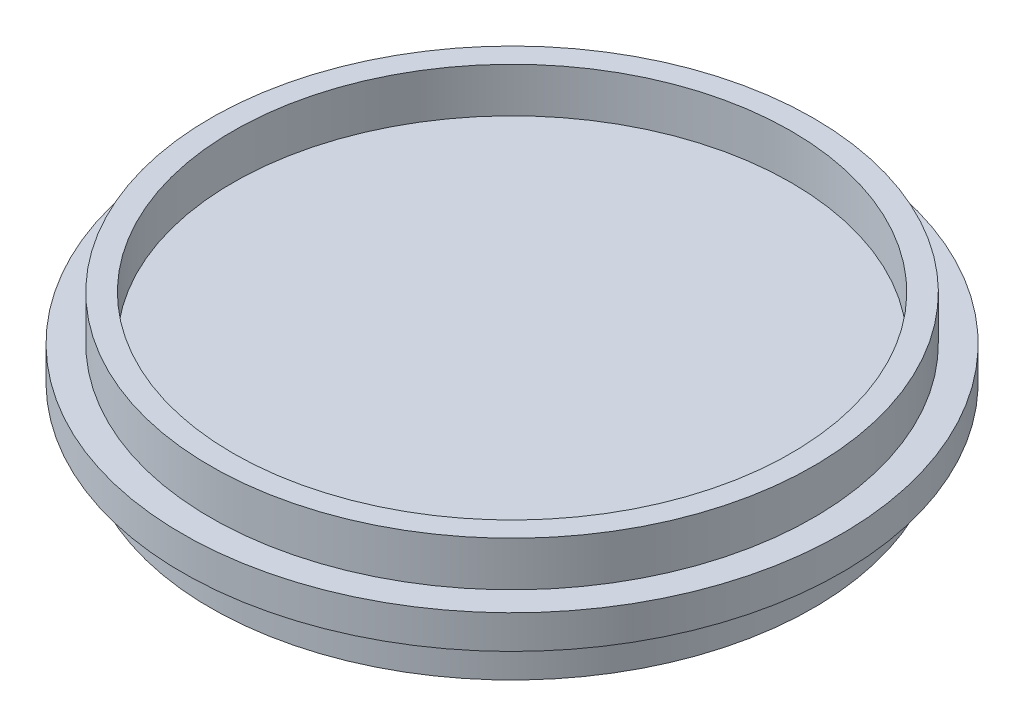
SolidWorks part; units mm, degrees
material "6061-T6 (SS)"
ref_plane "Front Plane" through (0, 0, 0) normal (0, 0, 1) x (1, 0, 0)
ref_plane "Top Plane" through (0, 0, 0) normal (0, 1, 0) x (1, 0, 0)
ref_plane "Right Plane" through (0, 0, 0) normal (1, 0, 0) x (0, 0, -1)
sketch "Sketch1" plane through (0, 0, 0) normal (0, 1, 0) x (1, 0, 0)
  line L5 (0, 0) -> (127.635, 0)
  line L6 (0, 0) -> (0, 127.635)
  line L7 (0, 127.635) -> (127.635, 127.635)
  line L8 (127.635, 0) -> (127.635, 127.635)
  dimension "D1" = 127.635
  dimension "D2" = 127.635
extrude "Boss-Extrude1" add sketch "Sketch1" along normal blind 9.525 contours L5 L8 L7 L6
sketch "Sketch12" plane through (0, 0, 0) normal (0, -1, 0) x (1, 0, 0)
  line L0 (63.8175, 0) -> (63.8175, -127.635) construction
  line L1 (0, 0) -> (127.635, 0) construction
  line L2 (0, -127.635) -> (127.635, -127.635) construction
  line L3 (0, -63.8175) -> (127.635, -63.8175) construction
  line L4 (0, 0) -> (0, -127.635) construction
  line L5 (127.635, 0) -> (127.635, -127.635) construction
  circle A0 centre (63.8175, -63.8175) radius 93.726
  dimension "D1" = 187.452
extrude "Boss-Extrude2" add sketch "Sketch12" against normal up to surface (9.525 mm away) contours A0 up to face at (63.8175, 9.525, -63.8175)
sketch "Sketch5" plane through (0, 9.525, 0) normal (0, 1, 0) x (1, 0, 0)
  circle A0 centre (63.8175, 63.8175) radius 46.355
  circle A3 centre (63.8175, 63.8175) radius 93.726 construction
  dimension "D1" = 92.71
extrude "Cut-Extrude1" [suppressed] cut sketch "Sketch5" against normal blind 9.525
sketch "Sketch11" [suppressed] plane through (0, 9.525, 0) normal (0, 1, 0) x (1, 0, 0)
  line L0 (63.8175, 63.8175) -> (63.8175, 115.443) construction
  circle A0 centre (63.8175, 115.443) radius 1.4351
  dimension "D2" = 2.8702
  dimension "D1" = 51.6255
extrude "Cut-Extrude3" [suppressed] cut sketch "Sketch11" against normal through all contours A0
pattern_circular "CirPattern1" [suppressed] count 12 over 360
sketch "Sketch14" [suppressed] plane through (0, 9.525, 0) normal (0, -1, 0) x (1, 0, 0)
  line L0 (63.8175, -63.8175) -> (147.6375, -63.8175) construction
  line L1 (0, -19.2087) -> (0, 19.2087) construction
  line L2 (147.6375, -63.8175) -> (152.7175, -63.8175)
  line L3 (136.3808, -105.7742) -> (140.8401, -108.2104)
  circle A0 centre (63.8175, -63.8175) radius 46.355 construction
  arc A2 (147.6375, -63.8175) -> (136.3808, -105.7742) centre (63.8175, -63.8175) cw
  arc A3 (152.7175, -63.8175) -> (140.8401, -108.2104) centre (63.8175, -63.8175) cw
  point P0 (63.8175, -63.8175)
  dimension "D1" = 83.82
  dimension "D2" = 88.9
  dimension "D3" = 46.482
  dimension "D4" = 43.942
ref_plane "Support mirror reference plane" through (0, 4.7625, 0) normal (0, 1, 0) x (1, 0, 0)
sketch "Sketch25" [suppressed] plane through (0, 9.525, 0) normal (0, -1, 0) x (1, 0, 0)
  line L0 (63.8175, -63.8175) -> (123.0872, -4.5478) construction
  line L2 (123.0872, -4.5478) -> (126.6793, -0.9557)
  line L3 (144.7953, -42.1754) -> (149.6712, -40.7448)
  line L5 (63.8175, -63.8175) -> (147.6375, -63.8175) construction
  arc A2 (123.0872, -4.5478) -> (144.7953, -42.1754) centre (63.8175, -63.8175) cw
  arc A3 (126.6793, -0.9557) -> (149.6712, -40.7448) centre (63.8175, -63.8175) cw
  point P0 (63.8175, -63.8175)
  dimension "D1" = 83.82
  dimension "D2" = 88.9
  dimension "D3" = 46.482
  dimension "D4" = 43.942
  dimension "D5" = 45
sketch "Sketch30" plane through (0, 0, 0) normal (0, -1, 0) x (1, 0, 0)
  circle A0 centre (63.8175, -63.8175) radius 85.725
  circle A1 centre (63.8175, -63.8175) radius 79.375
  dimension "D1" = 171.45
  dimension "D2" = 158.75
extrude "Boss-Extrude3" add sketch "Sketch30" along normal blind 12.7
mirror "Mirror1" about plane through (0, 4.7625, 0) normal (0, 1, 0) of "Boss-Extrude3"
sketch "Sketch31" plane through (0, 0, 0) normal (0, -1, 0) x (-1, 0, 0)
  line L0 (-63.8175, -52.481) -> (-63.8175, 177.7216) construction
ref_plane "Plane1" through (0, 0, -149.5425) normal (0, 0, -1) x (-1, 0, 0)
ref_plane "Plane2" through (63.8175, 0, 0) normal (-1, 0, 0) x (0, 0, -1)
sketch "Sketch32" plane through (0, 0, -149.5425) normal (0, 0, -1) x (-1, 0, 0)
  line L4 (-63.8175, -87.3125) -> (-63.8175, 87.3125) construction
  line L5 (-149.5425, 0) -> (21.9075, 0) construction
  line L6 (21.9075, 9.525) -> (-149.5425, 9.525) construction
  circle A0 centre (-63.8175, -6.35) radius 1.4351
  circle A1 centre (-63.8175, 15.875) radius 1.4351
  dimension "D1" = 2.8702
  dimension "D2" = 2.8702
  dimension "D3" = 6.35
  dimension "D4" = 6.35
extrude "Cut-Extrude4" [suppressed] cut sketch "Sketch32" against normal blind 15.24
pattern_circular "CirPattern2" [suppressed] count 12 over 360
